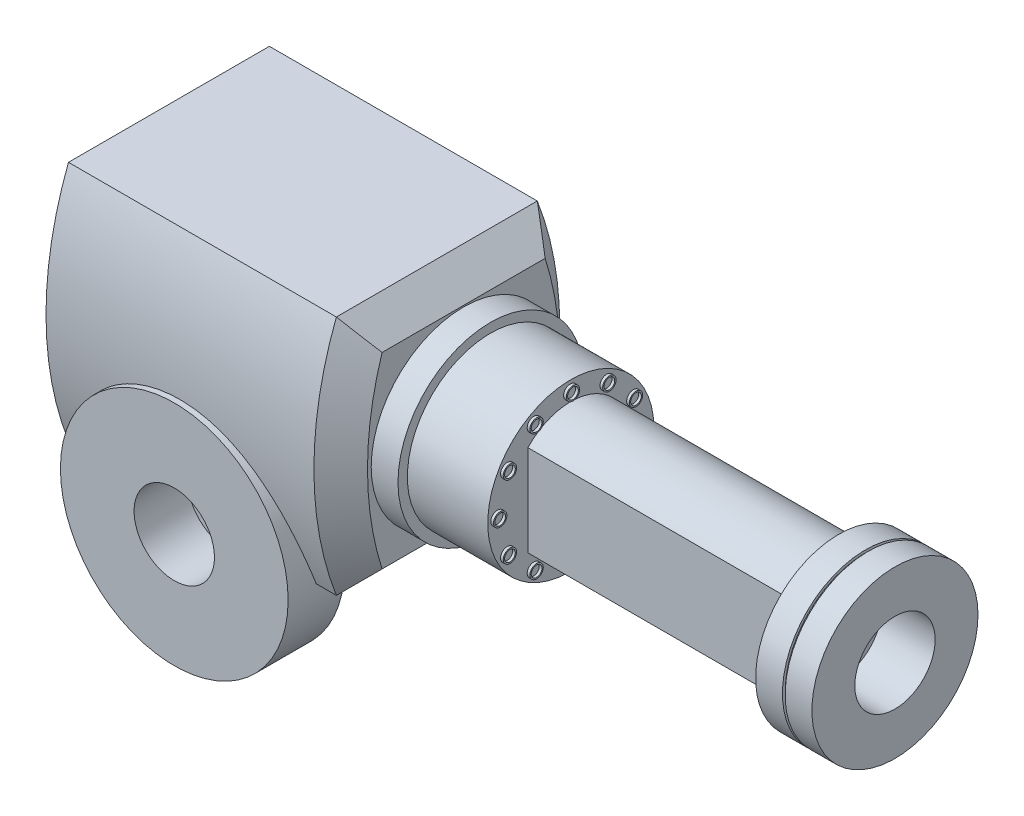
SolidWorks part; units mm, degrees
ref_plane "Front Plane" through (0, 0, 0) normal (0, 0, 1) x (1, 0, 0)
ref_plane "Top Plane" through (0, 0, 0) normal (0, 1, 0) x (1, 0, 0)
ref_plane "Right Plane" through (0, 0, 0) normal (1, 0, 0) x (0, 0, -1)
sketch "Sketch1" plane through (0, 0, 0) normal (1, 0, 0) x (0, 0, -1)
  line L0 (-63, 0) -> (102.0789, 0) construction
  line L1 (0, 58.5) -> (0, -71.0526) construction
  line L2 (-37.5, 45) -> (37.5, 45)
  line L3 (37.5, -45) -> (-37.5, -45)
  arc A0 (37.5, 45) -> (37.5, -45) centre (-79.119, 0) cw
  arc A1 (-37.5, 45) -> (-37.5, -45) centre (79.119, 0) ccw
  point P11 (0, -45)
  point P13 (0, 45)
  dimension "D5" = 125
  dimension "D1" = 45
  dimension "D2" = 45
  dimension "D3" = 37.5
  dimension "D4" = 37.5
extrude "Boss-Extrude1" add sketch "Sketch1" along normal blind 100
sketch "Sketch2" plane through (100, 0, 0) normal (1, 0, 0) x (0, 0, -1)
  line L2 (37.5, 45) -> (-37.5, 45)
  line L3 (-37.5, -45) -> (37.5, -45)
  line L4 (37.5, 45) -> (-37.5, 45)
  line L5 (-37.5, -45) -> (37.5, -45)
  arc A2 (37.5, -45) -> (37.5, 45) centre (-79.119, 0) ccw
  arc A3 (-37.5, 45) -> (-37.5, -45) centre (79.119, 0) ccw
  arc A4 (37.5, -45) -> (37.5, 45) centre (-79.119, 0) ccw
  arc A5 (-37.5, 45) -> (-37.5, -45) centre (79.119, 0) ccw
  dimension "D1" = 0
extrude "Boss-Extrude2" add sketch "Sketch2" along normal blind 10 draft 45
sketch "Sketch3" plane through (110, 0, 0) normal (1, 0, 0) x (0, 0, -1)
  circle A0 centre (0, 0) radius 34.5
  dimension "D1" = 69
extrude "Boss-Extrude3" add sketch "Sketch3" along normal blind 10
sketch "Sketch4" plane through (120, 0, 0) normal (1, 0, 0) x (0, 0, -1)
  circle A0 centre (0, 0) radius 31
  dimension "D1" = 62
extrude "Boss-Extrude4" add sketch "Sketch4" along normal blind 30
sketch "Sketch5" plane through (150, 0, 0) normal (1, 0, 0) x (0, 0, -1)
  circle A0 centre (27, 0) radius 2.5
  circle A1 centre (27, 0) radius 2
  dimension "D1" = 5
  dimension "D2" = 4
  dimension "D3" = 27
extrude "Boss-Extrude5" add sketch "Sketch5" along normal blind 1
pattern_circular "CirPattern1" count 12 over 360 about axis through (0, 0, 0.1767) along (1, 0, 0) of "Boss-Extrude5"
sketch "Sketch6" plane through (150, 0, 0) normal (1, 0, 0) x (0, 0, -1)
  line L0 (-15.2148, 0) -> (16, 0) construction
  line L1 (16, 0) -> (16, 17)
  line L2 (16, 0) -> (16, -17)
  line L3 (0, 17) -> (0, -18.3445) construction
  line L4 (-16, 0) -> (-16, -17)
  line L5 (-16, 0) -> (-16, 17)
  arc A0 (-16, 17) -> (16, 17) centre (0, 1.9003) cw
  arc A1 (-16, -17) -> (16, -17) centre (0, -1.9003) ccw
  dimension "D4" = 22
  dimension "D5" = 22
  dimension "D1" = 16
  dimension "D2" = 17
  dimension "D3" = 17
extrude "Boss-Extrude6" add sketch "Sketch6" along normal blind 100
sketch "Sketch7" plane through (250, 0, 0) normal (1, 0, 0) x (0, 0, -1)
  circle A0 centre (0, 0) radius 31
extrude "Boss-Extrude7" add sketch "Sketch7" along normal blind 10
sketch "Sketch8" plane through (260, 0, 0) normal (1, 0, 0) x (0, 0, -1)
  circle A0 centre (0, 0) radius 30
  circle A2 centre (0, 0) radius 31 construction
  dimension "D1" = 1
extrude "Boss-Extrude8" add sketch "Sketch8" along normal blind 1
sketch "Sketch9" plane through (261, 0, 0) normal (1, 0, 0) x (0, 0, -1)
  circle A0 centre (0, 0) radius 31
extrude "Boss-Extrude9" add sketch "Sketch9" along normal blind 10
ref_plane "Plane1" through (0, 0, 37.5) normal (0, 0, 1) x (1, 0, 0)
sketch "Sketch10" plane through (0, 0, 37.5) normal (0, 0, 1) x (1, 0, 0)
  line L0 (100, -45) -> (0, -45) construction
  circle A0 centre (50, -45) radius 42.5
  dimension "D1" = 85
extrude "Boss-Extrude10" add sketch "Sketch10" along normal mid plane 21
sketch "Sketch11" plane through (0, 0, 27) normal (0, 0, -1) x (-1, 0, 0)
  line L0 (-62.0656, -45) -> (-22.0656, -45)
  line L2 (-7.5, -45) -> (-92.5, -45) construction
  line L3 (-62.0656, -45) -> (-62.0656, -75)
  line L4 (-22.0656, -45) -> (-22.0656, -75)
  arc A0 (-62.0656, -75) -> (-22.0656, -75) centre (-42.0656, -52.6393) ccw
  point P4 (-50, -45)
  point P7 (-42.0656, -45)
  dimension "D4" = 30
  dimension "D1" = 40
  dimension "D2" = 30
  dimension "D3" = 30
extrude "Boss-Extrude11" add sketch "Sketch11" along normal blind 35
sketch "Sketch12" plane through (62.0656, 0, 0) normal (1, 0, 0) x (0, 0, -1)
  line L0 (8, -45) -> (33, -45)
  line L1 (8, -45) -> (8, -87)
  arc A0 (33, -45) -> (8, -87) centre (-21.8393, -40.7981) cw
  dimension "D3" = 55
  dimension "D1" = 25
  dimension "D2" = 42
extrude "Boss-Extrude12" add sketch "Sketch12" against normal blind 40
sketch "Sketch13" plane through (0, 0, -8) normal (0, 0, 1) x (1, 0, 0)
  line L3 (22.0656, -75) -> (22.0656, -87)
  line L4 (22.0656, -87) -> (62.0656, -87)
  line L5 (62.0656, -87) -> (62.0656, -75)
  line L6 (22.0656, -75) -> (22.0656, -87)
  line L7 (22.0656, -87) -> (62.0656, -87)
  line L8 (62.0656, -87) -> (62.0656, -75)
  arc A1 (22.0656, -75) -> (62.0656, -75) centre (42.0656, -52.6393) ccw
  arc A2 (22.0656, -75) -> (62.0656, -75) centre (42.0656, -52.6393) ccw
  dimension "D1" = 0
extrude "Cut-Extrude1" cut sketch "Sketch13" against normal blind 40
sketch "Sketch14" plane through (271, 0, 0) normal (1, 0, 0) x (0, 0, -1)
  circle A0 centre (0, 0) radius 15
  dimension "D1" = 30
extrude "Cut-Extrude2" cut sketch "Sketch14" against normal blind 20
sketch "Sketch15" plane through (0, 0, 48) normal (0, 0, 1) x (1, 0, 0)
  circle A0 centre (50, -45) radius 15
  dimension "D1" = 30
extrude "Cut-Extrude3" cut sketch "Sketch15" against normal blind 20
